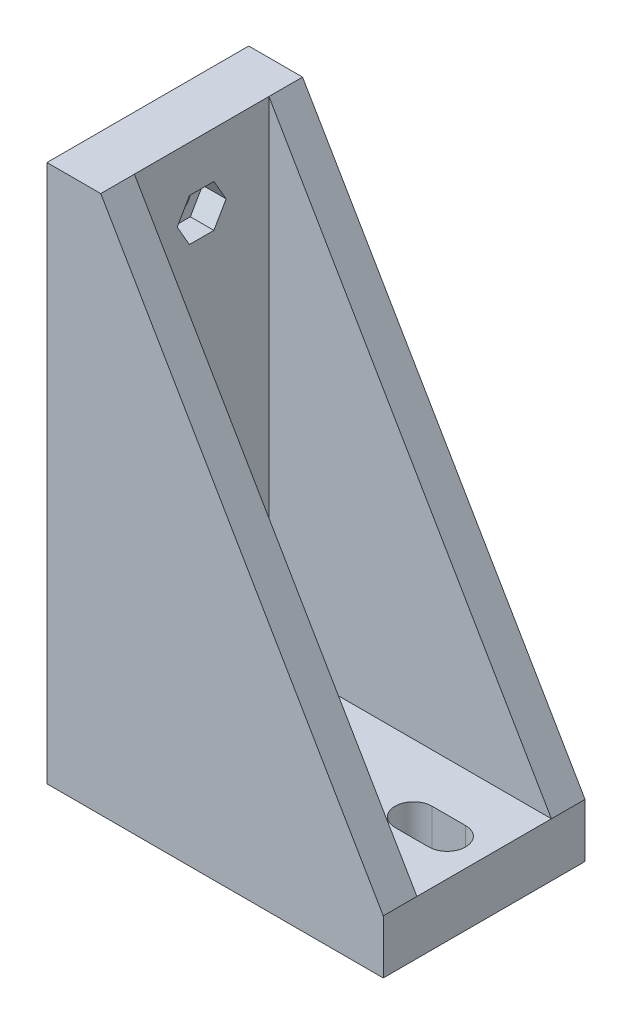
SolidWorks part; units mm, degrees
ref_plane "Front Plane" through (0, 0, 0) normal (0, 0, 1) x (1, 0, 0)
ref_plane "Top Plane" through (0, 0, 0) normal (0, 1, 0) x (1, 0, 0)
ref_plane "Right Plane" through (0, 0, 0) normal (1, 0, 0) x (0, 0, -1)
sketch "Sketch1" plane through (0, 0, 0) normal (0, 0, 1) x (1, 0, 0)
  line L0 (0, 0) -> (0, 80)
  line L1 (0, 80) -> (8, 80)
  line L2 (8, 80) -> (8, 8)
  line L3 (8, 8) -> (50, 8)
  line L4 (50, 8) -> (50, 0)
  line L5 (50, 0) -> (0, 0)
  dimension "D1" = 8
  dimension "D2" = 8
  dimension "D3" = 80
  dimension "D4" = 50
extrude "Boss-Extrude1" add sketch "Sketch1" along normal mid plane 30
sketch "Sketch2" plane through (0, 0, 15) normal (0, 0, 1) x (1, 0, 0)
  line L0 (8, 80) -> (50, 8)
rib "Rib1" sketch "Sketch2" sketch "Sketch2" thickness 5 extrusion direction parallel to sketch draft on no parameters "D1"=5
mirror "Mirror1" about plane through (0, 0, 0) normal (0, 0, 1) of "Rib1"
sketch "Sketch3" plane through (8, 0, 0) normal (1, 0, 0) x (0, 0, -1)
  line L0 (-10, 80) -> (10, 80) construction
  point P0 (0, 70)
  dimension "D1" = 10
hole_wizard "M3 Clearance Hole1" positions "Sketch3" profile "Sketch4" hole size "M3" standard "ANSI Metric" end condition through all
sketch "Sketch4" plane through (8, 70, 0) normal (0, 1, 0) x (0, 0, -1)
  line L0 (0, 0) -> (0, 8)
  line L1 (0, 8) -> (1.8, 8)
  line L2 (1.8, 8) -> (1.8, 0)
  line L5 (1.8, 0) -> (0, 0)
  line L11 (0, -6.35) -> (0, 107.95) construction
  dimension "Thru Hole Dia." = 3.6
  dimension "Thru Hole Depth" = 8
sketch "Sketch6" plane through (8, 0, 0) normal (1, 0, 0) x (0, 0, -1)
  line L1 (3.6373, 70) -> (1.8187, 73.15)
  line L2 (1.8187, 73.15) -> (-1.8187, 73.15)
  line L3 (-1.8187, 73.15) -> (-3.6373, 70)
  line L4 (-3.6373, 70) -> (-1.8187, 66.85)
  line L5 (-1.8187, 66.85) -> (1.8187, 66.85)
  line L6 (1.8187, 66.85) -> (3.6373, 70)
  circle A0 centre (0, 70) radius 3.15 construction
  dimension "D1" = 6.3
extrude "Cut-Extrude2" cut sketch "Sketch6" against normal offset from surface (3.5 mm away) 4.5 up to face at (0, 70, -1.8)
sketch "Sketch7" plane through (0, 8, 0) normal (0, 1, 0) x (1, 0, 0)
  line L0 (39.5, 0) -> (44.5, 0) construction
  line L1 (39.5, 2.75) -> (44.5, 2.75)
  line L2 (39.5, -2.75) -> (44.5, -2.75)
  line L3 (50, -10) -> (50, 10) construction
  arc A0 (39.5, 2.75) -> (39.5, -2.75) centre (39.5, 0) ccw
  arc A1 (44.5, -2.75) -> (44.5, 2.75) centre (44.5, 0) ccw
  point P2 (42, 0)
  dimension "D1" = 5.5
  dimension "D2" = 5
  dimension "D3" = 8
extrude "Cut-Extrude3" cut sketch "Sketch7" against normal through all contours A0 L2 A1 L1
